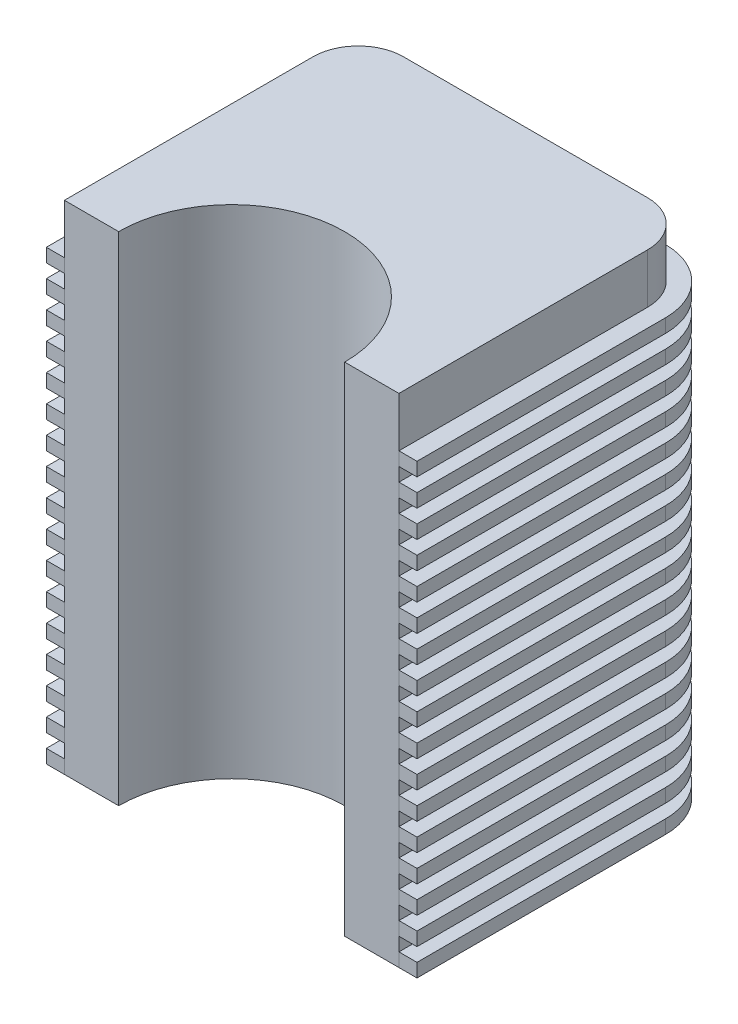
SolidWorks part; units mm, degrees
ref_plane "Front Plane" through (0, 0, 0) normal (0, 0, 1) x (1, 0, 0)
ref_plane "Top Plane" through (0, 0, 0) normal (0, 1, 0) x (1, 0, 0)
ref_plane "Right Plane" through (0, 0, 0) normal (1, 0, 0) x (0, 0, -1)
sketch "Sketch1" plane through (0, 0, 0) normal (0, 1, 0) x (1, 0, 0)
  line L0 (25, 0) -> (37, 0)
  line L1 (37, 0) -> (37, 55)
  line L2 (27, 65) -> (-27, 65)
  line L3 (0, 0) -> (0, 90.8775) construction
  line L4 (-25, 0) -> (-37, 0)
  line L5 (-37, 0) -> (-37, 55)
  arc A0 (25, 0) -> (-25, 0) centre (0, 0) ccw
  arc A1 (37, 55) -> (27, 65) centre (27, 55) ccw
  arc A2 (-37, 55) -> (-27, 65) centre (-27, 55) cw
  point P11 (0, 65)
  point P13 (37, 65)
  point P16 (-37, 65)
  dimension "D1" = 50
  dimension "D4" = 10
  dimension "D2" = 12
  dimension "D3" = 65
extrude "Boss-Extrude1" add sketch "Sketch1" along normal blind 110
sketch "Sketch3" plane through (0, 0, 0) normal (0, -1, 0) x (-1, 0, 0)
  line L0 (37, 0) -> (37, 55)
  line L6 (25, 0) -> (37, 0)
  line L7 (37, 0) -> (37, 55)
  line L8 (27, 65) -> (-27, 65)
  line L9 (-37, 55) -> (-37, 0)
  line L10 (-37, 0) -> (-25, 0)
  line L12 (37, 0) -> (37, 55)
  line L13 (27, 65) -> (-27, 65)
  line L14 (-37, 55) -> (-37, 0)
  line L16 (37, 0) -> (41, 0)
  line L17 (-37, 0) -> (-41, 0)
  line L21 (20.6155, -4) -> (41, -4)
  line L22 (41, -4) -> (41, 55)
  line L23 (27, 69) -> (-27, 69)
  line L24 (-41, 55) -> (-41, -4)
  line L25 (-41, -4) -> (-20.6155, -4)
  line L27 (41, 0) -> (41, 55)
  line L28 (27, 69) -> (-27, 69)
  line L29 (-41, 55) -> (-41, 0)
  arc A3 (25, 0) -> (-25, 0) centre (0, 0) ccw
  arc A4 (37, 55) -> (27, 65) centre (27, 55) ccw
  arc A5 (-27, 65) -> (-37, 55) centre (-27, 55) ccw
  arc A7 (37, 55) -> (27, 65) centre (27, 55) ccw
  arc A8 (-27, 65) -> (-37, 55) centre (-27, 55) ccw
  arc A12 (20.6155, -4) -> (-20.6155, -4) centre (0, 0) ccw
  arc A13 (41, 55) -> (27, 69) centre (27, 55) ccw
  arc A14 (-27, 69) -> (-41, 55) centre (-27, 55) ccw
  arc A16 (41, 55) -> (27, 69) centre (27, 55) ccw
  arc A17 (-27, 69) -> (-41, 55) centre (-27, 55) ccw
  line M20 (37, 0) -> (37, 55)
  arc M21 (37, 55) -> (27, 65) centre (27, 55) ccw
  line M22 (27, 65) -> (-27, 65)
  arc M23 (-27, 65) -> (-37, 55) centre (-27, 55) ccw
  line M24 (-37, 55) -> (-37, 0)
  dimension "D1" = 0
  dimension "D2" = 4
extrude "Boss-Extrude3" add sketch "Sketch3" against normal blind 3 separate body contours L28 A17 L29 L17 L16 L27 A16 M24 M23 M22 M21 M20
pattern_linear "LPattern1" count 17 spacing 6 along (0, 1, 0) of "Boss-Extrude3"
